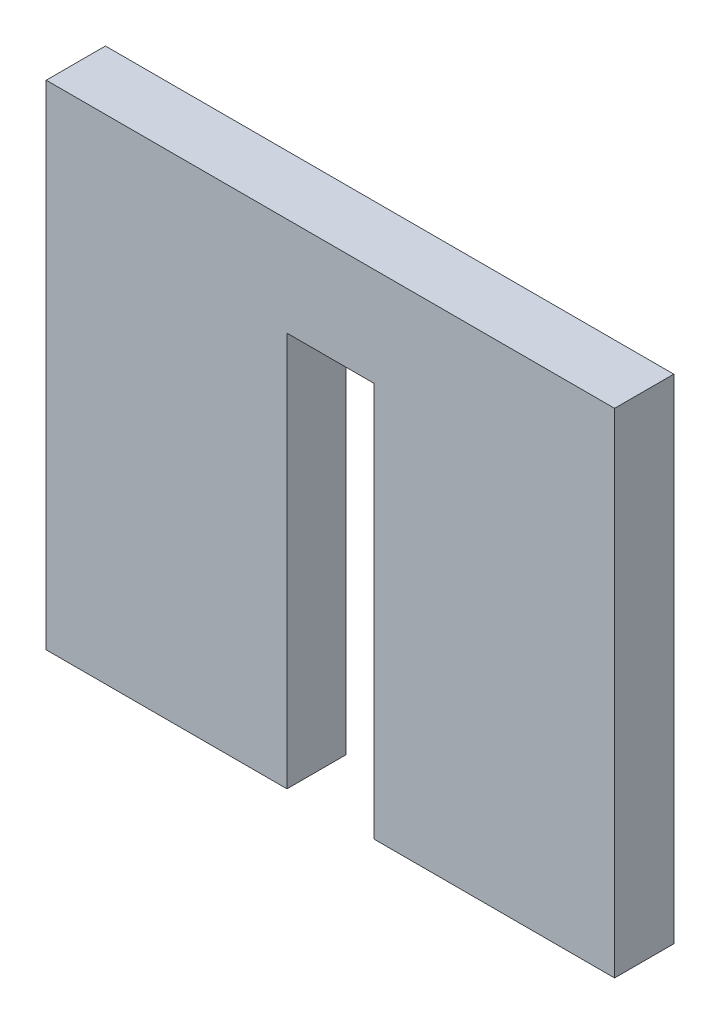
SolidWorks part; units mm, degrees
ref_plane "Front Plane" through (0, 0, 0) normal (0, 0, 1) x (1, 0, 0)
ref_plane "Top Plane" through (0, 0, 0) normal (0, 1, 0) x (1, 0, 0)
ref_plane "Right Plane" through (0, 0, 0) normal (1, 0, 0) x (0, 0, -1)
sketch "Sketch1" plane through (0, 0, 0) normal (0, 0, 1) x (1, 0, 0)
  line L0 (0, 0) -> (0, 25)
  line L1 (0, 25) -> (28.8, 25)
  line L2 (28.8, 25) -> (28.8, 0)
  line L3 (28.8, 0) -> (16.6, 0)
  line L4 (16.6, 0) -> (16.6, 20)
  line L5 (16.6, 20) -> (12.2, 20)
  line L6 (12.2, 20) -> (12.2, 0)
  line L7 (12.2, 0) -> (0, 0)
  dimension "D1" = 4.4
  dimension "D2" = 20
  dimension "D3" = 25
  dimension "D4" = 12.2
extrude "Boss-Extrude1" add sketch "Sketch1" along normal blind 3
